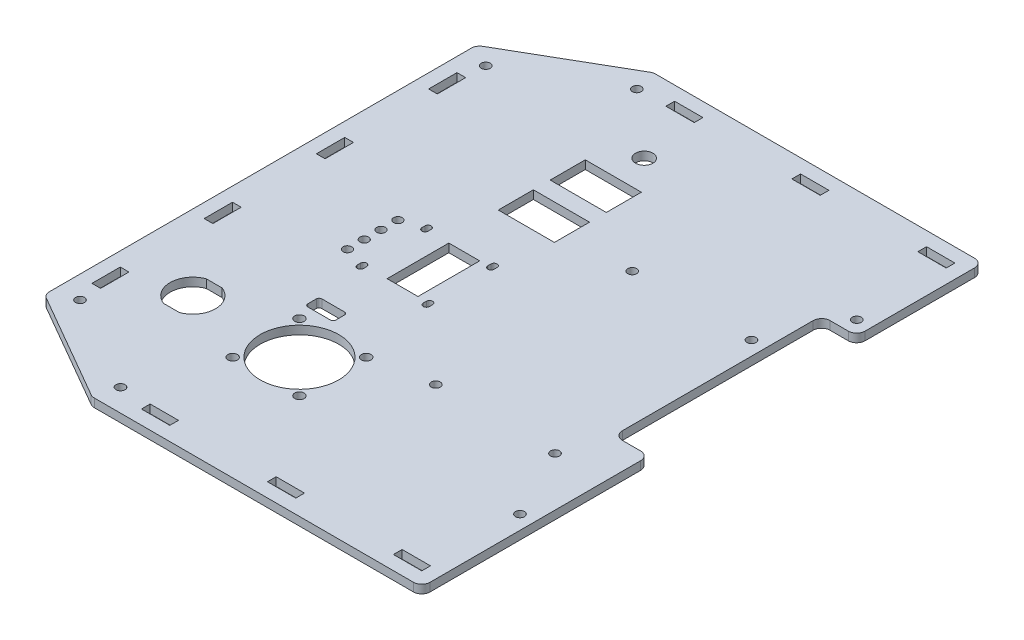
SolidWorks part; units mm, degrees
ref_plane "Front Plane" through (0, 0, 0) normal (0, 0, 1) x (1, 0, 0)
ref_plane "Top Plane" through (0, 0, 0) normal (0, 1, 0) x (1, 0, 0)
ref_plane "Right Plane" through (0, 0, 0) normal (1, 0, 0) x (0, 0, -1)
sketch "Sketch1" plane through (0, 0, 0) normal (0, 1, 0) x (1, 0, 0)
  line L0 (-85, 100) -> (85, 100) construction
  line L1 (-125, 100) -> (125, 100) construction
  line L2 (-125, 100) -> (-125, -100) construction
  line L3 (-125, -100) -> (125, -100) construction
  line L4 (125, 100) -> (125, -100) construction
  line L5 (85, 100) -> (125, 76.906) construction
  line L6 (125, 76.906) -> (125, -76.906) construction
  line L8 (-125, -76.906) -> (-125, 76.906) construction
  line L9 (-125, 76.906) -> (-85, 100) construction
  line L10 (-125, 0) -> (125, 0) construction
  line L11 (85, -100) -> (125, -76.906) construction
  line L12 (-85, -100) -> (85, -100) construction
  line L13 (-125, -76.906) -> (-85, -100) construction
  line L15 (-42.5, 100) -> (42.5, 100) construction
  line L16 (-42.5, 100) -> (-42.5, 65) construction
  line L17 (-42.5, 65) -> (42.5, 65) construction
  line L18 (42.5, 100) -> (42.5, 65) construction
  line L19 (42.5, -100) -> (42.5, -65) construction
  line L20 (-42.5, -65) -> (42.5, -65) construction
  line L21 (-42.5, -100) -> (-42.5, -65) construction
  line L22 (-42.5, -100) -> (42.5, -100) construction
  line L41 (32.5, -100) -> (32.5, 100)
  line L42 (-85, 100) -> (-125, 76.906)
  line L43 (-125, 76.906) -> (-125, -76.906)
  line L44 (-125, -76.906) -> (-85, -100)
  line L45 (-85, -100) -> (32.5, -100)
  line L46 (32.5, 100) -> (-85, 100)
  line L59 (-57.851, 11) -> (-68.851, 11) construction
  line L60 (-57.851, -11) -> (-57.851, 11) construction
  line L61 (-68.851, 11) -> (-68.851, -11) construction
  line L62 (-68.851, -11) -> (-57.851, -11) construction
  line L63 (-54.901, 12.05) -> (-54.901, 10.95) construction
  line L64 (-52.701, 10.95) -> (-52.701, 12.05) construction
  line L65 (-54.901, -10.95) -> (-54.901, -12.05) construction
  line L66 (-52.701, -12.05) -> (-52.701, -10.95) construction
  line L67 (-78.401, -10.95) -> (-78.401, -12.05) construction
  line L68 (-76.201, -12.05) -> (-76.201, -10.95) construction
  line L69 (-78.401, 12.05) -> (-78.401, 10.95) construction
  line L70 (-76.201, 10.95) -> (-76.201, 12.05) construction
  line L71 (-68.851, -11) -> (-57.851, -11)
  line L72 (-57.851, -11) -> (-57.851, 11)
  line L73 (-68.851, 11) -> (-68.851, -11)
  line L74 (-57.851, 11) -> (-68.851, 11)
  line L75 (-76.201, -12.05) -> (-76.201, -10.95)
  line L76 (-78.401, -10.95) -> (-78.401, -12.05)
  line L77 (-54.901, -10.95) -> (-54.901, -12.05)
  line L78 (-52.701, -12.05) -> (-52.701, -10.95)
  line L79 (-52.701, 10.95) -> (-52.701, 12.05)
  line L80 (-54.901, 12.05) -> (-54.901, 10.95)
  line L81 (-76.201, 10.95) -> (-76.201, 12.05)
  line L82 (-78.401, 12.05) -> (-78.401, 10.95)
  arc A16 (-52.701, 12.05) -> (-54.901, 12.05) centre (-53.801, 12.05) ccw construction
  arc A17 (-54.901, 10.95) -> (-52.701, 10.95) centre (-53.801, 10.95) ccw construction
  arc A18 (-52.701, -10.95) -> (-54.901, -10.95) centre (-53.801, -10.95) ccw construction
  arc A19 (-54.901, -12.05) -> (-52.701, -12.05) centre (-53.801, -12.05) ccw construction
  arc A20 (-76.201, -10.95) -> (-78.401, -10.95) centre (-77.301, -10.95) ccw construction
  arc A21 (-78.401, -12.05) -> (-76.201, -12.05) centre (-77.301, -12.05) ccw construction
  arc A22 (-76.201, 12.05) -> (-78.401, 12.05) centre (-77.301, 12.05) ccw construction
  arc A23 (-78.401, 10.95) -> (-76.201, 10.95) centre (-77.301, 10.95) ccw construction
  arc A24 (-78.401, -12.05) -> (-76.201, -12.05) centre (-77.301, -12.05) ccw
  arc A25 (-76.201, -10.95) -> (-78.401, -10.95) centre (-77.301, -10.95) ccw
  arc A26 (-54.901, -12.05) -> (-52.701, -12.05) centre (-53.801, -12.05) ccw
  arc A27 (-52.701, -10.95) -> (-54.901, -10.95) centre (-53.801, -10.95) ccw
  arc A28 (-54.901, 10.95) -> (-52.701, 10.95) centre (-53.801, 10.95) ccw
  arc A29 (-52.701, 12.05) -> (-54.901, 12.05) centre (-53.801, 12.05) ccw
  arc A30 (-78.401, 10.95) -> (-76.201, 10.95) centre (-77.301, 10.95) ccw
  arc A31 (-76.201, 12.05) -> (-78.401, 12.05) centre (-77.301, 12.05) ccw
  spline S0 degree 3 poles (-50.026, -38.959) (-50.026, -42.359) (-46.626, -42.359) (-46.626, -38.959) (-46.626, -35.559) (-50.026, -35.559) (-50.026, -38.959) (-50.026, -42.359) (-46.626, -42.359) knots -0.5 0 0 0 0.5 0.5 0.5 1 1 1 1.5 1.5 1.5 weights 1 0.333333 0.333333 1 0.333333 0.333333 1 0.333333 0.333333 only from (-50.026, -38.959) to (-50.026, -38.959) construction
  spline S1 degree 3 poles (-50.026, -62.759) (-50.026, -66.159) (-46.626, -66.159) (-46.626, -62.759) (-46.626, -59.359) (-50.026, -59.359) (-50.026, -62.759) (-50.026, -66.159) (-46.626, -66.159) knots -0.5 0 0 0 0.5 0.5 0.5 1 1 1 1.5 1.5 1.5 weights 1 0.333333 0.333333 1 0.333333 0.333333 1 0.333333 0.333333 only from (-50.026, -62.759) to (-50.026, -62.759) construction
  spline S2 degree 3 poles (-73.826, -62.759) (-73.826, -66.159) (-70.426, -66.159) (-70.426, -62.759) (-70.426, -59.359) (-73.826, -59.359) (-73.826, -62.759) (-73.826, -66.159) (-70.426, -66.159) knots -0.5 0 0 0 0.5 0.5 0.5 1 1 1 1.5 1.5 1.5 weights 1 0.333333 0.333333 1 0.333333 0.333333 1 0.333333 0.333333 only from (-73.826, -62.759) to (-73.826, -62.759) construction
  spline S3 degree 3 poles (-73.826, -38.959) (-73.826, -42.359) (-70.426, -42.359) (-70.426, -38.959) (-70.426, -35.559) (-73.826, -35.559) (-73.826, -38.959) (-73.826, -42.359) (-70.426, -42.359) knots -0.5 0 0 0 0.5 0.5 0.5 1 1 1 1.5 1.5 1.5 weights 1 0.333333 0.333333 1 0.333333 0.333333 1 0.333333 0.333333 only from (-73.826, -38.959) to (-73.826, -38.959) construction
  spline S4 degree 3 poles (-50.026, -38.959) (-50.026, -42.359) (-46.626, -42.359) (-46.626, -38.959) (-46.626, -35.559) (-50.026, -35.559) (-50.026, -38.959) (-50.026, -42.359) (-46.626, -42.359) knots -0.5 0 0 0 0.5 0.5 0.5 1 1 1 1.5 1.5 1.5 weights 1 0.333333 0.333333 1 0.333333 0.333333 1 0.333333 0.333333 only from (-50.026, -38.959) to (-50.026, -38.959)
  spline S5 degree 3 poles (-50.026, -62.759) (-50.026, -66.159) (-46.626, -66.159) (-46.626, -62.759) (-46.626, -59.359) (-50.026, -59.359) (-50.026, -62.759) (-50.026, -66.159) (-46.626, -66.159) knots -0.5 0 0 0 0.5 0.5 0.5 1 1 1 1.5 1.5 1.5 weights 1 0.333333 0.333333 1 0.333333 0.333333 1 0.333333 0.333333 only from (-50.026, -62.759) to (-50.026, -62.759)
  spline S6 degree 3 poles (-73.826, -62.759) (-73.826, -66.159) (-70.426, -66.159) (-70.426, -62.759) (-70.426, -59.359) (-73.826, -59.359) (-73.826, -62.759) (-73.826, -66.159) (-70.426, -66.159) knots -0.5 0 0 0 0.5 0.5 0.5 1 1 1 1.5 1.5 1.5 weights 1 0.333333 0.333333 1 0.333333 0.333333 1 0.333333 0.333333 only from (-73.826, -62.759) to (-73.826, -62.759)
  spline S7 degree 3 poles (-73.826, -38.959) (-73.826, -42.359) (-70.426, -42.359) (-70.426, -38.959) (-70.426, -35.559) (-73.826, -35.559) (-73.826, -38.959) (-73.826, -42.359) (-70.426, -42.359) knots -0.5 0 0 0 0.5 0.5 0.5 1 1 1 1.5 1.5 1.5 weights 1 0.333333 0.333333 1 0.333333 0.333333 1 0.333333 0.333333 only from (-73.826, -38.959) to (-73.826, -38.959)
  spline S8 degree 3 poles (-72.8629, -56.8847) (-73.764, -54.9949) (-74.226, -52.9527) (-74.226, -50.859) knots 0 0 0 0 1 1 1 1 weights 1 0.98357 0.98357 1 construction
  spline S9 degree 3 poles (-72.8629, -56.8847) (-72.5466, -57.548) (-72.1792, -58.1844) (-71.7629, -58.79) knots 0 0 0 0 1 1 1 1 weights 1 0.997939 0.997939 1 construction
  spline S10 degree 3 poles (-48.6891, -58.79) (-54.8172, -67.7043) (-65.6348, -67.7043) (-71.7629, -58.79) knots 0 0 0 0 1 1 1 1 weights 1 0.710999 0.710999 1 construction
  spline S11 degree 3 poles (-48.6891, -58.79) (-48.2728, -58.1844) (-47.9054, -57.548) (-47.5891, -56.8847) knots 0 0 0 0 1 1 1 1 weights 1 0.997939 0.997939 1 construction
  spline S12 degree 3 poles (-59.126, -36.9023) (-59.8586, -36.8445) (-60.5934, -36.8445) (-61.326, -36.9023) knots 0 0 0 0 1 1 1 1 weights 1 0.997939 0.997939 1 construction
  spline S13 degree 3 poles (-59.126, -36.9023) (-48.3419, -37.7522) (-42.9332, -47.1205) (-47.5891, -56.8847) knots 0 0 0 0 1 1 1 1 weights 1 0.710999 0.710999 1 construction
  spline S14 degree 3 poles (-74.226, -50.859) (-74.226, -43.1606) (-69.0006, -37.5072) (-61.326, -36.9023) knots 0 0 0 0 1 1 1 1 weights 1 0.822907 0.822907 1 construction
  spline S15 degree 3 poles (-72.8629, -56.8847) (-73.764, -54.9949) (-74.226, -52.9527) (-74.226, -50.859) knots 0 0 0 0 1 1 1 1 weights 1 0.98357 0.98357 1
  spline S16 degree 3 poles (-72.8629, -56.8847) (-72.5466, -57.548) (-72.1792, -58.1844) (-71.7629, -58.79) knots 0 0 0 0 1 1 1 1 weights 1 0.997939 0.997939 1
  spline S17 degree 3 poles (-48.6891, -58.79) (-54.8172, -67.7043) (-65.6348, -67.7043) (-71.7629, -58.79) knots 0 0 0 0 1 1 1 1 weights 1 0.710999 0.710999 1
  spline S18 degree 3 poles (-48.6891, -58.79) (-48.2728, -58.1844) (-47.9054, -57.548) (-47.5891, -56.8847) knots 0 0 0 0 1 1 1 1 weights 1 0.997939 0.997939 1
  spline S19 degree 3 poles (-59.126, -36.9023) (-59.8586, -36.8445) (-60.5934, -36.8445) (-61.326, -36.9023) knots 0 0 0 0 1 1 1 1 weights 1 0.997939 0.997939 1
  spline S20 degree 3 poles (-59.126, -36.9023) (-48.3419, -37.7522) (-42.9332, -47.1205) (-47.5891, -56.8847) knots 0 0 0 0 1 1 1 1 weights 1 0.710999 0.710999 1
  spline S21 degree 3 poles (-74.226, -50.859) (-74.226, -43.1606) (-69.0006, -37.5072) (-61.326, -36.9023) knots 0 0 0 0 1 1 1 1 weights 1 0.822907 0.822907 1
  point P4 (0, 100)
  point P6 (-125, 0)
  point P9 (0, 0)
  point P22 (0, 65)
  dimension "D1" = 250
  dimension "D2" = 200
  dimension "D3" = 60
  dimension "D4" = 60
  dimension "D5" = 40
  dimension "D6" = 85
  dimension "D7" = 35
  dimension "D8" = 20
extrude "Boss-Extrude1" add sketch "Sketch1" along normal blind 3
sketch "Sketch5" plane through (0, 3, 0) normal (0, 1, 0) x (1, 0, 0)
  line L0 (32.5, -40) -> (-32.5, -40) construction
  line L1 (32.5, 40) -> (-32.5, 40) construction
  line L2 (32.5, 40) -> (32.5, -40) construction
  line L4 (-32.5, 40) -> (-32.5, -40) construction
  line L10 (-32.5, 40) -> (-32.5, -40) construction
  line L14 (-27.5, 35) -> (15, 35) construction
  line L15 (-27.5, 35) -> (-27.5, -35) construction
  line L16 (-27.5, -35) -> (15, -35) construction
  line L17 (15, 35) -> (15, -35) construction
  circle A2 centre (-27.5, 35) radius 1.6
  circle A3 centre (15, 35) radius 1.6
  circle A4 centre (-27.5, -35) radius 1.6
  circle A5 centre (15, -35) radius 1.6
  point P4 (0, -40)
  point P6 (-32.5, 0)
  dimension "D4" = 3.2
  dimension "D1" = 65
  dimension "D2" = 80
  dimension "D5" = 5
  dimension "D3" = 5
  dimension "D6" = 5
  dimension "D7" = 17.5
extrude "Cut-Extrude2" cut sketch "Sketch5" against normal through all
sketch "Sketch6" plane through (0, 3, 0) normal (0, 1, 0) x (1, 0, 0)
  line L1 (-75.226, -28.859) -> (-65.226, -28.859)
  line L2 (-75.226, -28.859) -> (-75.226, -33.859)
  line L3 (-75.226, -33.859) -> (-65.226, -33.859)
  line L4 (-65.226, -28.859) -> (-65.226, -33.859)
  line L5 (-75.226, -35.859) -> (-45.226, -35.859) construction
  line L6 (-75.226, -35.859) -> (-75.226, -65.859) construction
  line L7 (-75.226, -65.859) -> (-45.226, -65.859) construction
  line L8 (-45.226, -35.859) -> (-45.226, -65.859) construction
  point P8 (-60.226, -50.859)
  point P11 (-60.226, -35.859)
  point P12 (-75.226, -50.859)
  dimension "D1" = 10
  dimension "D2" = 5
  dimension "D3" = 30
  dimension "D4" = 2
extrude "Cut-Extrude3" cut sketch "Sketch6" against normal through all
fillet "Fillet2" radius 1 4 edges at (-65.226, 1.5, 33.859) (-75.226, 1.5, 33.859) (-65.226, 1.5, 28.859) (-75.226, 1.5, 28.859)
sketch "Sketch8" plane through (0, 3, 0) normal (0, 1, 0) x (1, 0, 0)
  line L0 (-46.226, -50.859) -> (-74.226, -50.859) construction
  line L1 (-70.226, 42.5) -> (-50.226, 42.5)
  line L2 (-70.226, 42.5) -> (-70.226, 30)
  line L3 (-70.226, 30) -> (-50.226, 30)
  line L4 (-50.226, 42.5) -> (-50.226, 30)
  line L5 (-70.226, 48.5) -> (-50.226, 48.5)
  line L6 (-70.226, 48.5) -> (-70.226, 61)
  line L7 (-70.226, 61) -> (-50.226, 61)
  line L8 (-50.226, 48.5) -> (-50.226, 61)
  arc A0 (-47.5891, -56.8847) -> (-59.126, -36.9023) centre (-60.226, -50.859) ccw construction
  arc A1 (-61.326, -36.9023) -> (-74.226, -50.859) centre (-60.226, -50.859) ccw construction
  circle A2 centre (-60.226, 72) radius 3.1
  point P17 (-60.226, 30)
  point P18 (-60.226, -50.859)
  point P22 (-60.226, 61)
  dimension "D4" = 6.2
  dimension "D1" = 20
  dimension "D2" = 12.5
  dimension "D3" = 6
  dimension "D5" = 11
  dimension "D6" = 30
extrude "Cut-Extrude5" cut sketch "Sketch8" against normal through all
sketch "Sketch11" plane through (0, 3, 0) normal (0, 1, 0) x (1, 0, 0)
  line L0 (-101.0278, -43.259) -> (-95.4242, -43.259)
  line L1 (-101.0278, -58.459) -> (-95.4242, -58.459)
  circle A0 centre (-98.226, -50.859) radius 8.1
  point P2 (-60.226, -50.859)
  dimension "D1" = 16.2
  dimension "D2" = 15.2
  dimension "D3" = 38
extrude "Cut-Extrude8" cut sketch "Sketch11" against normal through all contours L1 A0 L0
sketch "Sketch12" plane through (0, 3, 0) normal (0, 1, 0) x (1, 0, 0)
  line L0 (-85, 9) -> (-85, 3) construction
  line L1 (-85, 3) -> (-85, -3) construction
  line L2 (-85, -3) -> (-85, -9) construction
  line L3 (-125, 76.906) -> (-125, -76.906) construction
  circle A0 centre (-85, 9) radius 1.55
  circle A1 centre (-85, 3) radius 1.55
  circle A2 centre (-85, -3) radius 1.55
  circle A3 centre (-85, -9) radius 1.55
  point P8 (-85, 0)
  dimension "D1" = 3.1
  dimension "D2" = 18
  dimension "D3" = 40
extrude "Cut-Extrude9" cut sketch "Sketch12" against normal through all
sketch "Sketch13" plane through (0, 3, 0) normal (0, 1, 0) x (1, 0, 0)
  line L4 (-125, -76.906) -> (-85, -100) construction
  line L5 (-85, -100) -> (32.5, -100) construction
  line L6 (-125, 76.906) -> (-125, -76.906) construction
  line L7 (-85, 100) -> (-125, 76.906) construction
  line L8 (32.5, 100) -> (-85, 100) construction
  circle A0 centre (27.5, 60) radius 1.6
  circle A1 centre (27.5, -60) radius 1.6
  circle A2 centre (-82.8564, -92) radius 1.6
  circle A3 centre (-117, -72.2872) radius 1.6
  circle A4 centre (-117, 72.2872) radius 1.6
  circle A5 centre (-82.8564, 92) radius 1.6
  dimension "D1" = 3.2
  dimension "D6" = 8
  dimension "D7" = 8
  dimension "D8" = 8
  dimension "D9" = 8
  dimension "D10" = 8
  dimension "D11" = 8
  dimension "D12" = 8
  dimension "D13" = 8
extrude "Cut-Extrude10" cut sketch "Sketch13" against normal up to next
sketch "Sketch14" plane through (0, 3, 0) normal (0, 1, 0) x (1, 0, 0)
  line L0 (-125, 76.906) -> (-125, -76.906) construction
  line L1 (-120, 65.05) -> (-116.9, 65.05)
  line L2 (-120, 65.05) -> (-120, 54.95)
  line L3 (-120, 54.95) -> (-116.9, 54.95)
  line L4 (-116.9, 65.05) -> (-116.9, 54.95)
  line L5 (-120, 25.05) -> (-116.9, 25.05)
  line L6 (-120, 25.05) -> (-120, 14.95)
  line L7 (-120, 14.95) -> (-116.9, 14.95)
  line L8 (-116.9, 25.05) -> (-116.9, 14.95)
  line L9 (-120, -14.95) -> (-116.9, -14.95)
  line L10 (-120, -14.95) -> (-120, -25.05)
  line L11 (-120, -25.05) -> (-116.9, -25.05)
  line L12 (-116.9, -14.95) -> (-116.9, -25.05)
  line L13 (-120, -54.95) -> (-116.9, -54.95)
  line L14 (-120, -54.95) -> (-120, -65.05)
  line L15 (-120, -65.05) -> (-116.9, -65.05)
  line L16 (-116.9, -54.95) -> (-116.9, -65.05)
  line L17 (-118.45, 14.95) -> (-118.45, -14.95) construction
  point P18 (-116.9, 20)
  point P19 (-116.9, -20)
  point P20 (-116.9, 60)
  point P21 (-116.9, -60)
  point P24 (-118.45, 0)
  dimension "D1" = 3.1
  dimension "D2" = 10.1
  dimension "D3" = 5
  dimension "D4" = 40
  dimension "D5" = 40
  dimension "D6" = 40
extrude "Cut-Extrude11" cut sketch "Sketch14" against normal through all
sketch "Sketch15" plane through (0, 3, 0) normal (0, 1, 0) x (1, 0, 0)
  line L0 (32.5, -100) -> (32.5, 100) construction
  line L1 (32.5, 55) -> (20, 55)
  line L2 (32.5, 55) -> (32.5, -19)
  line L3 (32.5, -19) -> (20, -19)
  line L4 (20, 55) -> (20, -19)
  line L5 (32.5, 100) -> (-85, 100) construction
  dimension "D1" = 74
  dimension "D2" = 12.5
  dimension "D3" = 45
extrude "Cut-Extrude12" cut sketch "Sketch15" against normal through all
fillet "Fillet3" radius 3 10 edges at (32.5, 1.5, -100) (-85, 1.5, -100) (-125, 1.5, -76.906) (-125, 1.5, 76.906) (-85, 1.5, 100) (32.5, 1.5, 100) (20, 1.5, -55) (32.5, 1.5, -55) (20, 1.5, 19) (32.5, 1.5, 19)
sketch "Sketch16" plane through (0, 3, 0) normal (0, 1, 0) x (1, 0, 0)
  line L0 (-84.1962, -100) -> (29.5, -100) construction
  line L13 (17.4, -91.9) -> (27.5, -91.9)
  line L14 (17.4, -91.9) -> (17.4, -95)
  line L15 (17.4, -95) -> (27.5, -95)
  line L16 (27.5, -91.9) -> (27.5, -95)
  line L34 (0, 0) -> (-125, 0) construction
  line L35 (-1.65, 0) -> (1.65, 0) construction
  line L36 (-125, 75.1739) -> (-125, -75.1739) construction
  line L37 (-27.5, -91.9) -> (-27.5, -95)
  line L38 (-27.5, -91.9) -> (-17.4, -91.9)
  line L39 (-17.4, -91.9) -> (-17.4, -95)
  line L40 (-27.5, -95) -> (-17.4, -95)
  line L41 (-72.4, -91.9) -> (-72.4, -95)
  line L42 (-72.4, -91.9) -> (-62.3, -91.9)
  line L43 (-62.3, -91.9) -> (-62.3, -95)
  line L44 (-72.4, -95) -> (-62.3, -95)
  line L45 (17.4, 95) -> (27.5, 95)
  line L46 (27.5, 91.9) -> (27.5, 95)
  line L47 (17.4, 91.9) -> (27.5, 91.9)
  line L48 (17.4, 91.9) -> (17.4, 95)
  line L49 (-27.5, 91.9) -> (-17.4, 91.9)
  line L50 (-17.4, 91.9) -> (-17.4, 95)
  line L51 (-27.5, 95) -> (-17.4, 95)
  line L52 (-27.5, 91.9) -> (-27.5, 95)
  line L53 (-72.4, 91.9) -> (-62.3, 91.9)
  line L54 (-62.3, 91.9) -> (-62.3, 95)
  line L55 (-72.4, 95) -> (-62.3, 95)
  line L56 (-72.4, 91.9) -> (-72.4, 95)
  dimension "D1" = 10.1
  dimension "D2" = 3.1
  dimension "D3" = 5
  dimension "D5" = 3
extrude "Cut-Extrude13" cut sketch "Sketch16" against normal through all
